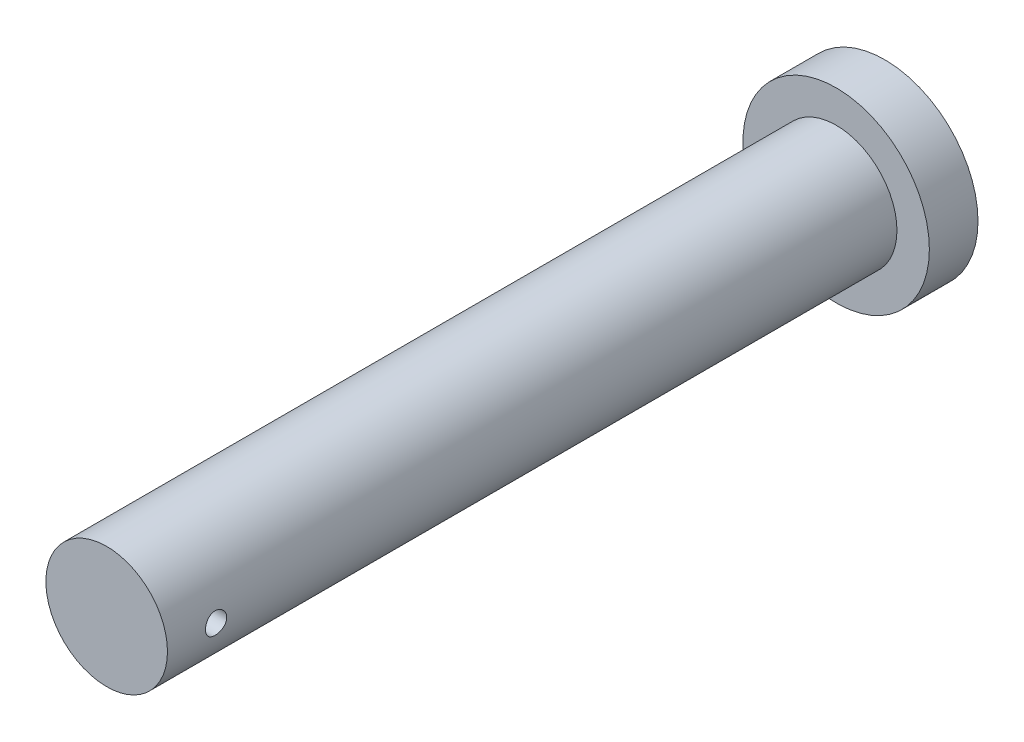
SolidWorks part; units mm, degrees
ref_plane "Front Plane" through (0, 0, 0) normal (0, 0, 1) x (1, 0, 0)
ref_plane "Top Plane" through (0, 0, 0) normal (0, 1, 0) x (1, 0, 0)
ref_plane "Right Plane" through (0, 0, 0) normal (1, 0, 0) x (0, 0, -1)
sketch "Sketch2" plane through (0, 0, 0) normal (0, 0, 1) x (1, 0, 0)
  circle A0 centre (0, 0) radius 23
  dimension "D1" = 46
extrude "Boss-Extrude1" add sketch "Sketch2" along normal blind 12
sketch "Sketch3" plane through (0, 0, 12) normal (0, 0, 1) x (1, 0, 0)
  circle A0 centre (0, 0) radius 15
  dimension "D1" = 30
extrude "Boss-Extrude2" add sketch "Sketch3" along normal blind 180
ref_plane "Plane1" through (0, 0, 180) normal (0, 0, 1) x (1, 0, 0)
sketch "Sketch4" plane through (0, 0, 180) normal (0, 0, 1) x (1, 0, 0)
  line L0 (-30, 0) -> (-30, 3)
  line L1 (-30, 3) -> (30, 2.5)
  line L2 (30, 2.5) -> (30, 0)
  line L3 (30, 0) -> (-30, 0)
  dimension "D1" = 60
  dimension "D2" = 3
  dimension "D3" = 2.5
  dimension "D4" = 30
revolve "Cut-Revolve1" cut sketch "Sketch4" angle 360 about L3
scale "Scale1" scale about centroid uniform scaling yes scale factor 0.3
